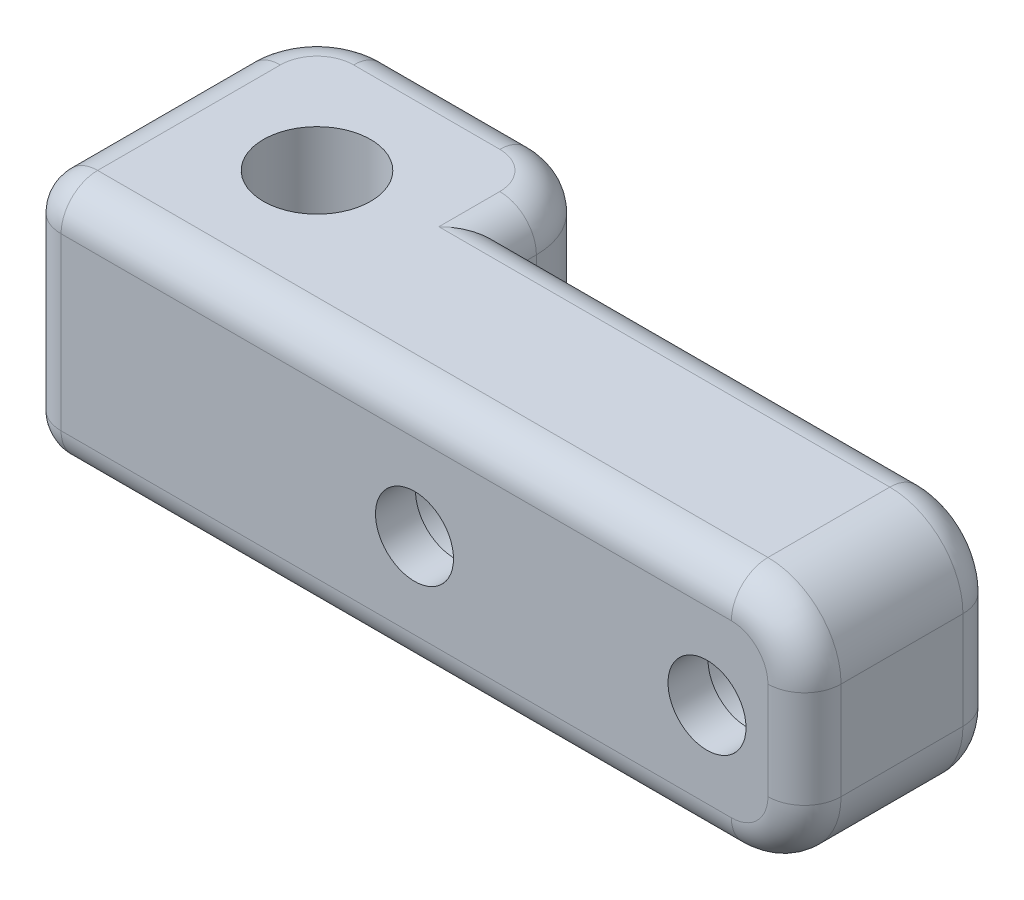
SolidWorks part; units mm, degrees
ref_plane "Front Plane" through (0, 0, 0) normal (0, 0, 1) x (1, 0, 0)
ref_plane "Top Plane" through (0, 0, 0) normal (0, 1, 0) x (1, 0, 0)
ref_plane "Right Plane" through (0, 0, 0) normal (1, 0, 0) x (0, 0, -1)
sketch "Sketch1" plane through (0, 0, 0) normal (0, 1, 0) x (1, 0, 0)
  line L1 (0, 0) -> (12, 0)
  line L2 (0, 0) -> (0, 12)
  line L3 (0, 12) -> (12, 12)
  line L4 (12, 0) -> (12, 12)
  dimension "D1" = 12
  dimension "D2" = 12
extrude "Boss-Extrude1" add sketch "Sketch1" along normal blind 10
sketch "Sketch2" plane through (0, 10, 0) normal (0, 1, 0) x (1, 0, 0)
  line L0 (12, 12) -> (0, 12) construction
  line L1 (0, 12) -> (0, 0) construction
  circle A0 centre (6, 6) radius 1.5
  point P0 (6, 6)
  dimension "D1" = 3
  dimension "D2" = 6
  dimension "D3" = 6
sketch "Sketch3" plane through (12, 0, 0) normal (1, 0, 0) x (0, 0, -1)
  line L0 (0, 0) -> (12, 0) construction
  line L1 (0, 10) -> (8, 10)
  line L2 (0, 10) -> (0, 0)
  line L3 (0, 0) -> (8, 0)
  line L4 (8, 10) -> (8, 0)
  dimension "D1" = 8
extrude "Boss-Extrude3" add sketch "Sketch3" along normal blind 20
sketch "Sketch4" plane through (0, 0, 0) normal (0, 0, 1) x (1, 0, 0)
  line L0 (22, 10) -> (22, 0) construction
  line L3 (16, 5) -> (28, 5) construction
  line L6 (0, 10) -> (0, 0) construction
  point P7 (28, 5)
  point P8 (16, 5)
  point P9 (22, 5)
  dimension "D1" = 12
  dimension "D2" = 16
hole_wizard "M3 Clearance Hole1" positions "Sketch4" profile "Sketch5" hole size "M3" standard "ANSI Metric"
sketch "Sketch5" plane through (16, 5, 0) normal (1, 0, 0) x (0, -1, 0)
  line L0 (0, 0) -> (0, 12)
  line L1 (0, 12) -> (1.6, 12)
  line L2 (1.6, 12) -> (1.6, 0)
  line L5 (1.6, 0) -> (0, 0)
  line L11 (0, -6.35) -> (0, 107.95) construction
  dimension "Thru Hole Dia." = 3.2
  dimension "Thru Hole Depth" = 12
fillet "Fillet3" radius 3 4 edges at (32, 0, -4) (32, 10, -4) (0, 5, -12) (12, 5, -12)
sketch "Sketch6" plane through (0, 0, -8) normal (0, 0, -1) x (-1, 0, 0)
  point P0 (-28, 5)
  point P1 (-16, 5)
hole_wizard "Ø4.4 (4.4) Diameter Hole1" positions "Sketch6" profile "Sketch7" hole size "Ø4.4" standard "ANSI Metric"
sketch "Sketch7" plane through (28, 5, -8) normal (1, 0, 0) x (0, 1, 0)
  line L0 (0, 0) -> (0, 7.3219)
  line L1 (0, 7.3219) -> (2.2, 6)
  line L2 (2.2, 6) -> (2.2, 0)
  line L5 (2.2, 0) -> (0, 0)
  line L10 (0, 7.3219) -> (-2.2, 6) construction
  line L11 (0, -6.35) -> (0, 107.95) construction
  dimension "Hole Dia." = 4.4
  dimension "Hole Depth" = 6
  dimension "Drill Angle" = 118
fillet "Fillet4" radius 1.5 21 edges at (12, 0, -8.5) (11.1213, 0, -11.1213) (6, 0, -12) (0.8787, 0, -11.1213) (20.5, 0, -8) (31.1213, 0.8787, -8) (32, 5, -8) (31.1213, 9.1213, -8) (12, 10, -8.5) (11.1213, 10, -11.1213) (6, 10, -12) (0.8787, 10, -11.1213) (14.5, 0, 0) (31.1213, 0.8787, 0) (32, 5, 0) (31.1213, 9.1213, 0) (0, 0, -4.5) (20.5, 10, -8) (0, 10, -4.5) (14.5, 10, 0) (0, 5, 0)
hole_wizard "Hole1" positions "Sketch2" profile "Sketch8" legacy
sketch "Sketch8" plane through (6, 10, -6) normal (1, 0, 0) x (0, 0, 1)
  line L0 (0, 0) -> (0, 100)
  line L1 (0, 100) -> (1.6, 100)
  line L2 (1.6, 100) -> (1.6, 6)
  line L3 (1.6, 6) -> (2.2, 6)
  line L4 (2.2, 6) -> (2.2, 0)
  line L5 (2.2, 0) -> (0, 0)
  line L6 (0, 110) -> (0, -10) construction
  dimension "Diameter" = 3.2
  dimension "Depth" = 100
  dimension "C-Bore Diameter" = 4.4
  dimension "C-Bore Depth" = 6
sketch "Sketch9" plane through (0, 10, 0) normal (0, 1, 0) x (1, 0, 0)
  line L1 (4.3466, 8.7784) -> (2.7671, 5.9573)
  line L2 (2.7671, 5.9573) -> (4.4205, 3.1789)
  line L3 (4.4205, 3.1789) -> (7.6534, 3.2216)
  line L4 (7.6534, 3.2216) -> (9.2329, 6.0427)
  line L5 (9.2329, 6.0427) -> (7.5795, 8.8211)
  line L6 (7.5795, 8.8211) -> (4.3466, 8.7784)
  circle A0 centre (6, 6) radius 2.8 construction
  point P0 (6, 6)
  dimension "D1" = 5.6
extrude "Cut-Extrude1" [suppressed] cut sketch "Sketch9" against normal blind 2
